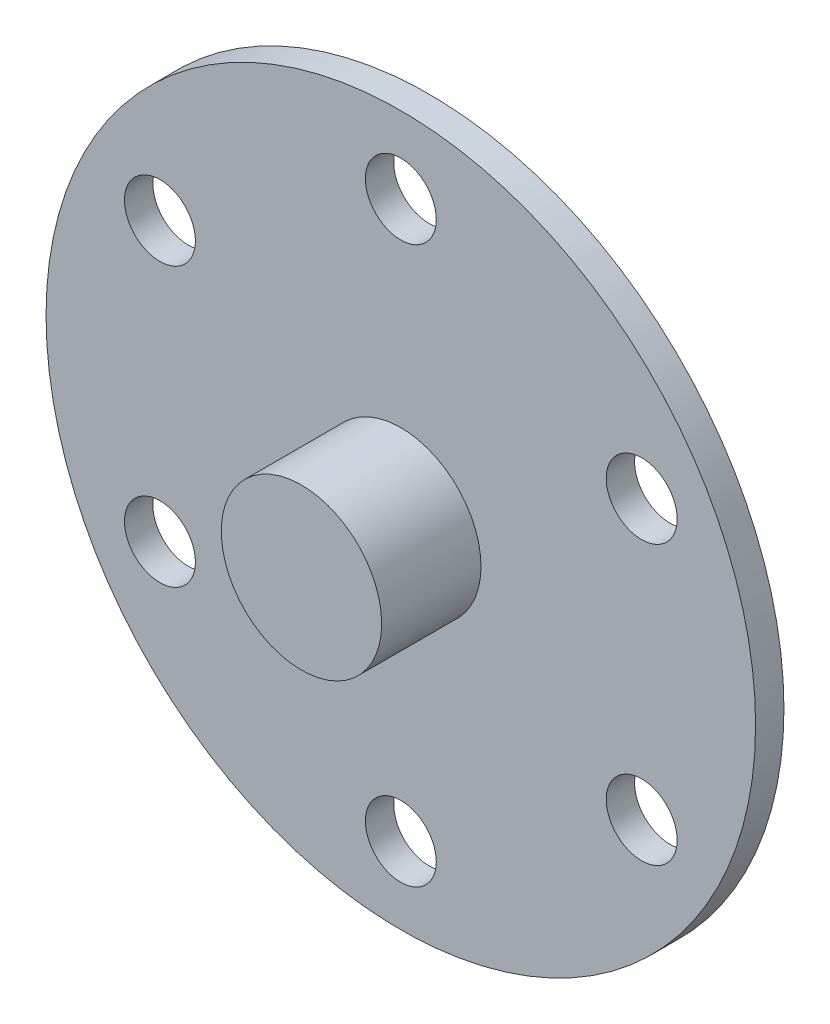
SolidWorks part; units mm, degrees
material "1060 Alloy"
ref_plane "Front" through (0, 0, 0) normal (0, 0, 1) x (1, 0, 0)
ref_plane "Top" through (0, 0, 0) normal (0, 1, 0) x (1, 0, 0)
ref_plane "Right" through (0, 0, 0) normal (1, 0, 0) x (0, 0, -1)
sketch "Sketch4" plane through (0, 0, 0) normal (0, 0, 1) x (1, 0, 0)
  circle A0 centre (0, 0) radius 63.5
extrude "Boss-Extrude1" add sketch "Sketch4" against normal blind 5.08
sketch "Sketch5" plane through (0, 0, 0) normal (0, 0, 1) x (1, 0, 0)
  circle A0 centre (0, 0) radius 14.351
extrude "Boss-Extrude2" add sketch "Sketch5" along normal blind 17.78
sketch "Sketch6" plane through (0, 0, 0) normal (0, 0, 1) x (1, 0, 0)
  line L0 (0, 63.5) -> (0, -63.5) construction
  line L1 (63.5, 0) -> (-63.5, 0) construction
  circle A0 centre (0, 0) radius 49.784 construction
  circle A1 centre (0, 0) radius 63.5 construction
  circle A2 centre (0, 49.784) radius 6.35
  circle A3 centre (43.1142, 24.892) radius 6.35
  circle A4 centre (43.1142, -24.892) radius 6.35
  circle A5 centre (0, -49.784) radius 6.35
  circle A6 centre (-43.1142, -24.892) radius 6.35
  circle A7 centre (-43.1142, 24.892) radius 6.35
  dimension "D1" = 6
extrude "Cut-Extrude1" cut sketch "Sketch6" against normal blind 17.78
